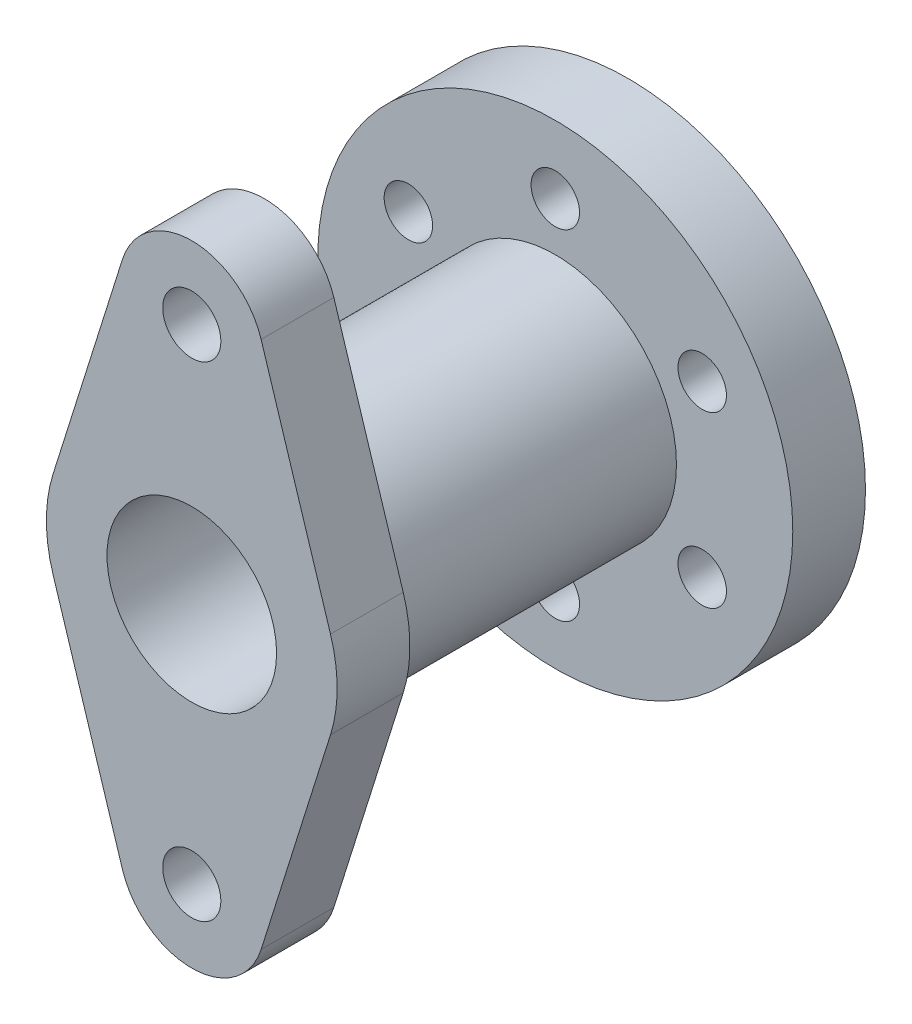
SolidWorks part; units mm, degrees
ref_plane "Alzado" through (0, 0, 0) normal (0, 0, 1) x (1, 0, 0)
ref_plane "Planta" through (0, 0, 0) normal (0, 1, 0) x (1, 0, 0)
ref_plane "Vista lateral" through (0, 0, 0) normal (1, 0, 0) x (0, 0, -1)
sketch "Croquis1" plane through (0, 0, 0) normal (0, 0, 1) x (1, 0, 0)
  circle A0 centre (0, 0) radius 49
  dimension "D1" = 98
extrude "Saliente-Extruir1" add sketch "Croquis1" along normal blind 15
sketch "Croquis2" plane through (0, 0, 15) normal (0, 0, 1) x (1, 0, 0)
  line L0 (0, 0) -> (0, 35) construction
  circle A0 centre (0, 35) radius 5
  circle A1 centre (30.3109, 17.5) radius 5
  circle A2 centre (30.3109, -17.5) radius 5
  circle A3 centre (0, -35) radius 5
  circle A4 centre (-30.3109, -17.5) radius 5
  circle A5 centre (-30.3109, 17.5) radius 5
  point P16 (0, 0)
  dimension "D2" = 10
  dimension "D1" = 35
  dimension "D3" = 6
extrude "Cortar-Extruir1" cut sketch "Croquis2" against normal through all
sketch "Croquis3" plane through (0, 0, 15) normal (0, 0, 1) x (1, 0, 0)
  circle A0 centre (0, 0) radius 25
  circle A1 centre (0, 0) radius 13
  dimension "D1" = 50
  dimension "D2" = 26
extrude "Saliente-Extruir2" add sketch "Croquis3" along normal blind 75
sketch "Croquis4" plane through (0, 0, 90) normal (0, 0, 1) x (1, 0, 0)
  line L0 (0, 0) -> (0, 50) construction
  line L5 (0, 0) -> (0, -50) construction
  line L6 (0, 0) -> (-49, 0) construction
  line L7 (14.3091, 54.5) -> (28.6182, 9)
  line L8 (14.3091, -54.5) -> (28.6182, -9)
  line L9 (-14.3091, 54.5) -> (-28.6182, 9)
  line L10 (-14.3091, -54.5) -> (-28.6182, -9)
  circle A0 centre (0, 50) radius 6
  arc A1 (14.3091, 54.5) -> (-14.3091, 54.5) centre (0, 50) ccw
  arc A3 (-28.6182, 9) -> (-28.6182, -9) centre (0, 0) ccw
  circle A4 centre (0, 0) radius 49 construction
  circle A5 centre (0, -50) radius 6
  arc A6 (-14.3091, -54.5) -> (14.3091, -54.5) centre (0, -50) ccw
  arc A7 (28.6182, -9) -> (28.6182, 9) centre (0, 0) ccw
  point P0 (0, 0)
  dimension "D3" = 12
  dimension "D4" = 30
  dimension "D5" = 12
  dimension "D6" = 60
  dimension "D7" = 30
  dimension "D1" = 50
extrude "Saliente-Extruir3" add sketch "Croquis4" against normal blind 15
sketch "Croquis5" plane through (0, 0, 90) normal (0, 0, 1) x (1, 0, 0)
  circle A0 centre (0, 0) radius 17.5
  dimension "D1" = 35
extrude "Cortar-Extruir2" cut sketch "Croquis5" against normal blind 30
